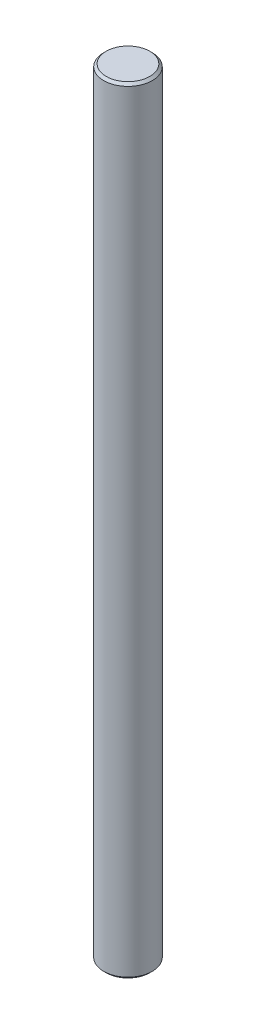
SolidWorks part; units mm, degrees
material "AISI 1045 Steel, cold drawn"
ref_plane "Front Plane" through (0, 0, 0) normal (0, 0, 1) x (1, 0, 0)
ref_plane "Top Plane" through (0, 0, 0) normal (0, 1, 0) x (1, 0, 0)
ref_plane "Right Plane" through (0, 0, 0) normal (1, 0, 0) x (0, 0, -1)
sketch "Sketch1" plane through (0, 0, 0) normal (0, 1, 0) x (1, 0, 0)
  circle A0 centre (0, 0) radius 2.5
  dimension "D1" = 5
extrude "Boss-Extrude1" add sketch "Sketch1" along normal mid plane 80
chamfer "Chamfer1" distance 0.25 angle 45 2 edges at (0, -40, 2.5) (0, 40, 2.5)
